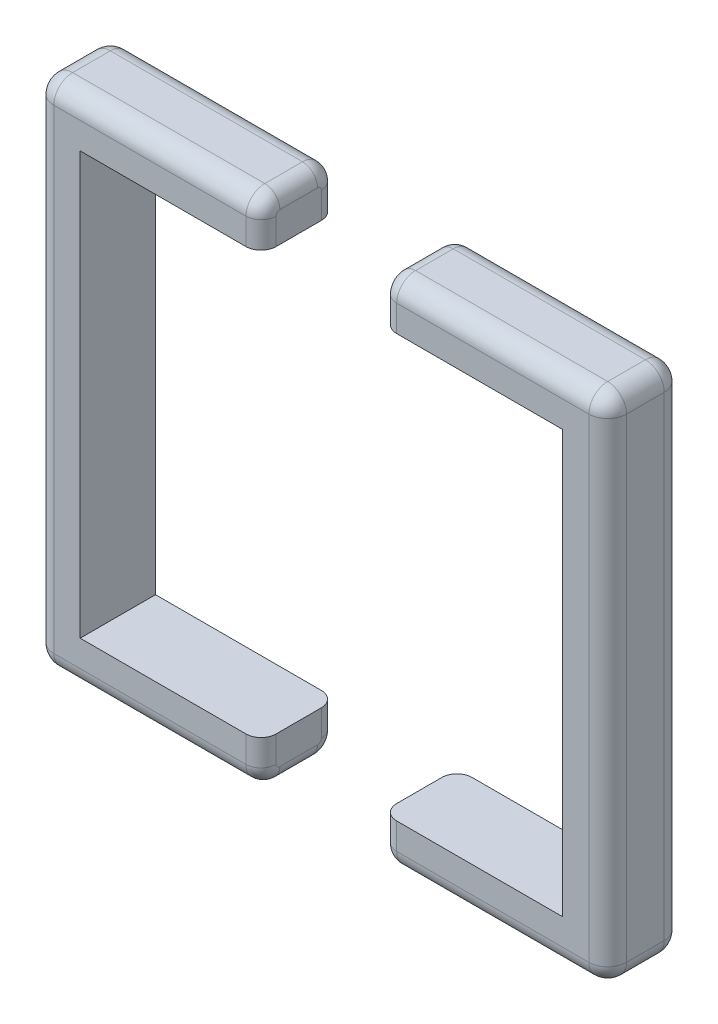
SolidWorks part; units mm, degrees
ref_plane "Front" through (0, 0, 0) normal (0, 0, 1) x (1, 0, 0)
ref_plane "Top" through (0, 0, 0) normal (0, 1, 0) x (1, 0, 0)
ref_plane "Right" through (0, 0, 0) normal (1, 0, 0) x (0, 0, -1)
sketch "Sketch1" plane through (0, 0, 0) normal (0, 0, 1) x (1, 0, 0)
  line L5 (0, 0) -> (-812.8, 0)
  line L6 (0, 0) -> (0, 711.2)
  line L7 (0, 711.2) -> (-812.8, 711.2)
  line L8 (-812.8, 0) -> (-812.8, 711.2)
  line L9 (-889, 787.4) -> (76.2, 787.4)
  line L10 (-889, 787.4) -> (-889, -76.2)
  line L11 (-889, -76.2) -> (76.2, -76.2)
  line L12 (76.2, 787.4) -> (76.2, -76.2)
  dimension "D1" = 812.8
  dimension "D2" = 711.2
  dimension "D3" = 76.2
  dimension "D4" = 76.2
  dimension "D5" = 76.2
  dimension "D6" = 76.2
extrude "Boss-Extrude1" add sketch "Sketch1" along normal blind 127
fillet "Fillet1" radius 31.75 12 edges at (-889, 355.6, 127) (-889, 355.6, 0) (-889, -76.2, 63.5) (-406.4, -76.2, 127) (-406.4, -76.2, 0) (-406.4, 787.4, 127) (-889, 787.4, 63.5) (-406.4, 787.4, 0) (76.2, -76.2, 63.5) (76.2, 355.6, 127) (76.2, 787.4, 63.5) (76.2, 355.6, 0)
sketch "Sketch2" plane through (0, 787.4, 0) normal (0, 1, 0) x (1, 0, 0)
  line L1 (-304.8, 0) -> (-508, 0)
  line L2 (-304.8, 0) -> (-304.8, -127)
  line L3 (-304.8, -127) -> (-508, -127)
  line L4 (-508, 0) -> (-508, -127)
  line L5 (44.45, -63.5) -> (-857.25, -63.5) construction
  line L6 (44.45, -127) -> (-857.25, -127) construction
  line L7 (-857.25, 0) -> (44.45, 0) construction
  line L8 (44.45, -95.25) -> (44.45, -31.75) construction
  line L9 (-857.25, -31.75) -> (-857.25, -95.25) construction
  point P14 (-406.4, -63.5)
  point P15 (-406.4, -127)
  dimension "D2" = 203.2
extrude "Cut-Extrude1" cut sketch "Sketch2" against normal up to surface (863.6 mm away) up to face at (-406.4, -76.2, 63.5)
fillet "Fillet2" radius 25.4 10 edges at (-304.8, -22.225, 0) (-304.8, -66.9006, 9.2994) (-304.8, -22.225, 127) (-304.8, -66.9006, 117.7006) (-304.8, 733.425, 127) (-304.8, 778.1006, 117.7006) (-304.8, 733.425, 0) (-304.8, 778.1006, 9.2994) (-304.8, -76.2, 63.5) (-304.8, 787.4, 63.5)
fillet "Fillet3" radius 25.4 10 edges at (-508, -22.225, 127) (-508, -66.9006, 117.7006) (-508, -22.225, 0) (-508, -66.9006, 9.2994) (-508, 733.425, 0) (-508, 778.1006, 9.2994) (-508, 733.425, 127) (-508, 778.1006, 117.7006) (-508, -76.2, 63.5) (-508, 787.4, 63.5)
